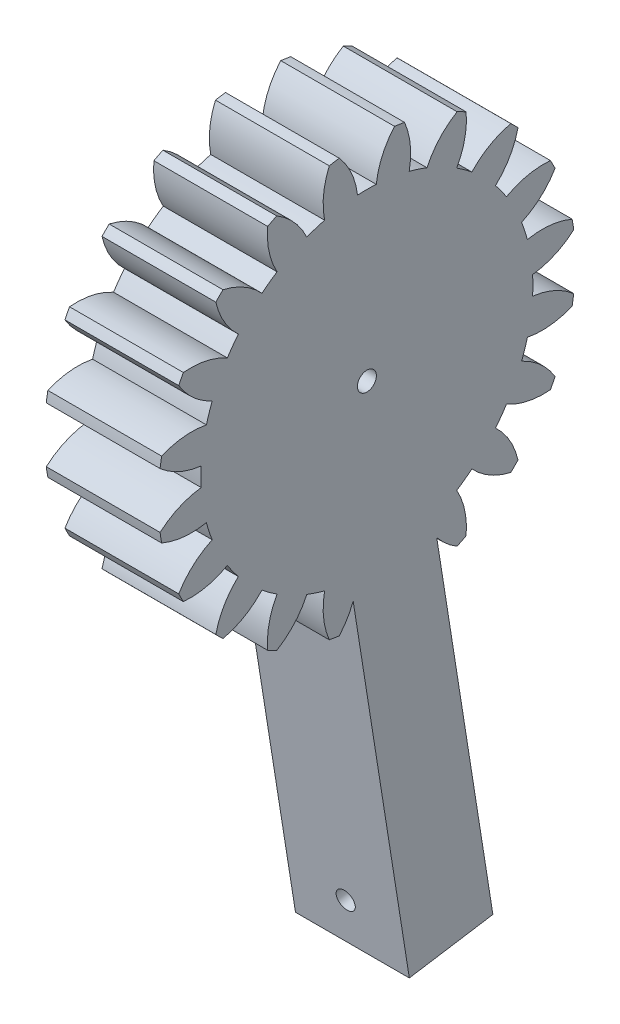
SolidWorks part; units mm, degrees
ref_plane "Plane1" through (0, 0, 0) normal (0, 0, 1) x (1, 0, 0)
ref_plane "Plane2" through (0, 0, 0) normal (0, 1, 0) x (1, 0, 0)
ref_plane "Plane3" through (0, 0, 0) normal (1, 0, 0) x (0, 0, -1)
other "Configuration Table"
sketch "HoldingSke" plane through (0, 0, 0) normal (0, 1, 0) x (1, 0, 0)
  line L0 (0, 0) -> (0.1879, -0.0684)
  line L1 (-15, 0) -> (100, 0) construction
  line L2 (0, 0) -> (-2.1039, 2.3779)
  line L3 (0, 0) -> (-11.863, 4.5341)
  line L4 (0, 0) -> (8.1152, 2.9537)
  line L5 (0, 0) -> (-46.8476, -17.4728)
  line L6 (0, 0) -> (-24.8689, -16.7791)
  line L7 (-2.1039, 2.3779) -> (8.6586, 51.2059)
  line L8 (-76.2, 54.61) -> (-75.3, 54.61)
  line L9 (-71.009, 38.7566) -> (-53.1078, 45.2721)
  line L10 (-76.2, 71.12) -> (104.1128, 71.12)
  line L11 (0, 0) -> (-30, 0)
  line L12 (-76.2, 101.6) -> (-76.033, 101.6)
  line L13 (24.9733, 27.94) -> (52.9518, 28.4284)
  line L14 (24.9733, 27.94) -> (24.9743, 27.94)
  line L15 (24.9733, 27.94) -> (100.4006, 29.5858)
  line L16 (-63.627, -5) -> (-12.827, -5)
  circle A0 centre (0, 0) radius 2.5
  circle A1 centre (0, 0) radius 37.5
  circle A2 centre (0, 0) radius 37.5
  circle A3 centre (0, 0) radius 2.5
  dimension "MHD" = 75
  dimension "Hub_dia" = 75
  dimension "Bore" = 5
  dimension "MBD" = 5
  dimension "Num_teeth" = 20
  dimension "Pitch" = 0.2
  dimension "Overall_len" = 50
  dimension "Show_teeth" = 20
  dimension "Thickness" = 30
  dimension "OAL" = 50.0001
  dimension "T_dim" = 0.9
  dimension "Ap" = 20
  dimension "H" = 19.05
  dimension "Pitch_radius" = 180.3128
  dimension "Width" = 30
  dimension "Backlash" = 0.167
  dimension "Addendum_fac" = 1
  dimension "Dedendum_fac" = 1.25
  dimension "Clearance_fac" = 0.25
  dimension "Dedendum_add" = 0.001
  dimension "Module" = 5
sketch "BasProSke" plane through (0, 0, 0) normal (0, 1, 0) x (1, 0, 0)
  line L0 (-10, 0) -> (60, 0) construction
  line L1 (0, 0) -> (0, 55)
  line L2 (0, 0) -> (30, 0)
  line L3 (30, 0) -> (30, 55)
  line L4 (30, 55) -> (0, 55)
  dimension "Thickness" = 30
  dimension "Diameter" = 110
revolve "Base-Revolve" add sketch "BasProSke" angle 360 about L0
sketch "TooCutSke" plane through (0, 0, 0) normal (1, 0, 0) x (0, 0, -1)
  line L1 (0, 0) -> (0, 107) construction
  line L2 (0, 0) -> (-4.2151, 49.822) construction
  line L3 (0, 0) -> (-15.6021, 98.5081) construction
  line L4 (-4.2151, 49.822) -> (-7.8011, 49.254) construction
  arc A0 (2.4648, 43.6795) -> (-2.4648, 43.6795) centre (0, 0) ccw
  arc A1 (7.3009, 54.5389) -> (-7.3009, 54.5389) centre (0, 0) ccw
  circle A2 centre (0, 0) radius 50 construction
  circle A3 centre (0, 0) radius 46.9846 construction
  arc A4 (-2.4648, 43.6795) -> (-7.3009, 54.5389) centre (-22.3276, 41.3405) ccw
  arc A5 (7.3009, 54.5389) -> (2.4648, 43.6795) centre (22.3276, 41.3405) ccw
  dimension "Root_dia" = 87.498
  dimension "Overcut_dia" = 110.0508
  dimension "Pitch_dia" = 100
  dimension "Base_dia" = 93.9693
  dimension "Flank_rad" = 20
  dimension "Half_ang" = 9
  dimension "Half_CT" = 3.6307
extrude "ToothCut" cut sketch "TooCutSke" along normal through all
fillet "Breaks" [suppressed] radius 0.1
fillet "RootFillets" [suppressed] radius 1.251
pattern_circular "TeethCuts" count 20 over 360 about axis through (0, 0, 0) along (1, 0, 0) of "ToothCut", "RootFillets", "Breaks"
sketch "HubNeaOneSke" plane through (0, 0, 0) normal (-1, 0, 0) x (0, 0, 1)
  circle A0 centre (0, 0) radius 37.5
  dimension "Diameter" = 75
extrude "HubNearOne" [suppressed] add sketch "HubNeaOneSke" along normal blind 20.0001
sketch "HubNeaBotSke" plane through (0, 0, 0) normal (-1, 0, 0) x (0, 0, 1)
  circle A0 centre (0, 0) radius 37.5
  dimension "Diameter" = 75
extrude "HubNearBoth" [suppressed] add sketch "HubNeaBotSke" along normal blind 10
ref_plane "FarPln" through (30, 0, 0) normal (1, 0, 0) x (0, 0, -1)
sketch "HubFarSke" plane through (30, 0, 0) normal (1, 0, 0) x (0, 0, -1)
  circle A0 centre (0, 0) radius 37.5
  dimension "Diameter" = 75
extrude "HubFar" [suppressed] add sketch "HubFarSke" along normal blind 10
sketch "BorSke" plane through (0, 0, 0) normal (1, 0, 0) x (0, 0, -1)
  circle A0 centre (0, 0) radius 2.5
  dimension "Diameter" = 5
extrude "Bore" cut sketch "BorSke" along normal mid plane 100.0001
sketch "KeySke" plane through (0, 0, 0) normal (1, 0, 0) x (0, 0, -1)
  line L0 (-1, 0) -> (-1, 3.4)
  line L1 (-1, 3.4) -> (1, 3.4)
  line L2 (1, 3.4) -> (1, 0)
  line L3 (0, 0) -> (0, 34) construction
  line L4 (-1, 0) -> (1, 0)
  dimension "Offset" = 3.4
  dimension "Width" = 2
extrude "Keyway" [suppressed] cut sketch "KeySke" along normal mid plane 100.0001
pattern_circular "Keyway2" [suppressed] count 2 every 90 about axis through (-10, 0, 0) along (1, 0, 0)
sketch "草图6" plane through (30, 0, 0) normal (1, 0, 0) x (0, 0, -1)
  line L3 (0, 50) -> (0, -50) construction
  line L4 (0, 0) -> (6.8439, -43.2104) construction
  line L5 (-4.4661, -43.0812) -> (11.1773, -141.85)
  line L6 (11.1773, -141.85) -> (33.2038, -138.3614)
  line L7 (33.2038, -138.3614) -> (17.5603, -39.5926)
  circle A0 centre (0, 0) radius 43.297 construction
  arc A2 (-4.4661, -43.0812) -> (17.5603, -39.5926) centre (-0.0707, 0.4464) ccw
  point P5 (-247.4407, -93.586)
  point P11 (0, 0)
  dimension "D2" = 22.301
  dimension "D3" = 0.452
  dimension "D4" = 86.594
  dimension "D5" = 43.749
  dimension "D1" = 100
extrude "凸台-拉伸1" add sketch "草图6" against normal up to surface (30 mm away) up to face at (0, 0, -2.5)
sketch "草图7" plane through (0, -1.7443, 11.0132) normal (0, -0.1564, 0.9877) x (1, 0, 0)
  line L0 (0, -141.8521) -> (30, -141.8521) construction
  line L3 (15, -141.8521) -> (15, -66.61) construction
  circle A0 centre (15, -130.5681) radius 2.5
  dimension "D1" = 5
  dimension "D2" = 11.284
extrude "切除-拉伸1" cut sketch "草图7" against normal through all both and the other way through all
equation "' \"Module@HoldingSke\" = 6.35"
equation "' \"Num_teeth@HoldingSke\" = 12"
equation "' \"Ap@HoldingSke\" =  20"
equation "' \"Ap@HoldingSke\" = 20"
equation "' \"Width@HoldingSke\" = 0.5 * 25.4"
equation "' \"Hub_dia@HoldingSke\"= 1 * 25.4"
equation "' \"Hub_dia@HoldingSke\" = 1 * 25.4"
equation "' \"Overall_len@HoldingSke\" = 1.0 * 25.4"
equation "' \"Bore@HoldingSke\" = 0.75 * 25.4"
equation "' \"T_dim@HoldingSke\" = 0.1 * 25.4"
equation "' \"Width@KeySke\" = 0.25 * 25.4"
equation "' \"Show_teeth@HoldingSke\" = 13"
equation "' \"Backlash@HoldingSke\" = 0.009 * 25.4"
equation "' \"Addendum_fac@HoldingSke\" = 1.0"
equation "' \"Dedendum_fac@HoldingSke\" = 1.25"
equation "' \"Dedendum_add@HoldingSke\" = 0.00005 * 25.4"
equation "' \"Clearance_fac@HoldingSke\" = 0.25"
equation "\"Pitch@HoldingSke\" = 1 / \"Module@HoldingSke\""
equation "\"Overcut_dia@TooCutSke\" = (\"Num_teeth@HoldingSke\" + 2 * \"Addendum_fac@HoldingSke\") / \"Pitch@HoldingSke\" + 0.002 * 25.4"
equation "\"Pitch_dia@TooCutSke\" = \"Num_teeth@HoldingSke\" / \"Pitch@HoldingSke\""
equation "\"Base_dia@TooCutSke\" = \"Num_teeth@HoldingSke\" / \"Pitch@HoldingSke\" * cos((\"Ap@HoldingSke\"  * 3.14159265 / 180))"
equation "\"Root_dia@TooCutSke\" = (\"Num_teeth@HoldingSke\" + 2) / \"Pitch@HoldingSke\" - 2 * (\"Addendum_fac@HoldingSke\" + \"Dedendum_fac@HoldingSke\") / \"Pitch@HoldingSke\" - \"Dedendum_add@HoldingSke\" * 2"
equation "\"Half_ang@TooCutSke\" = 180 / \"Num_teeth@HoldingSke\""
equation "\"Half_CT@TooCutSke\" = \"Num_teeth@HoldingSke\" / \"Pitch@HoldingSke\" * sin((3.14159265 / 2 / \"Num_teeth@HoldingSke\")) / 2 - 7 * \"Backlash@HoldingSke\" / 4"
equation "\"Flank_rad@TooCutSke\" = \"Num_teeth@HoldingSke\" / \"Pitch@HoldingSke\" / 5"
equation "\"Radius@RootFillets\" = \"Clearance_fac@HoldingSke\" / \"Pitch@HoldingSke\" + \"Dedendum_add@HoldingSke\""
equation "\"Break_rad@Breaks\" = 0.02 / \"Pitch@HoldingSke\""
equation "\"Thickness@HoldingSke\" = \"Width@HoldingSke\""
equation "\"OAL@HoldingSke\" = \"Thickness@HoldingSke\""
equation "\"MHD@HoldingSke\" = (\"Num_teeth@HoldingSke\" + 2) / \"Pitch@HoldingSke\" - 2 * (\"Addendum_fac@HoldingSke\" + \"Dedendum_fac@HoldingSke\")  / \"Pitch@HoldingSke\" - \"Dedendum_add@HoldingSke\" * 2"
equation "\"MBD@HoldingSke\" = (\"Num_teeth@HoldingSke\" + 2) / \"Pitch@HoldingSke\" - 2 * (\"Addendum_fac@HoldingSke\" + \"Dedendum_fac@HoldingSke\")  / \"Pitch@HoldingSke\" - \"Dedendum_add@HoldingSke\" * 2 - 0.002 * 25.4"
equation "\"MHD@HoldingSke\" = ((sgn( \"MHD@HoldingSke\" - \"Hub_dia@HoldingSke\" )-1)*( \"MHD@HoldingSke\" - \"Hub_dia@HoldingSke\" ))/-2+ \"Hub_dia@HoldingSke\""
equation "\"MBD@HoldingSke\" = ((sgn( \"MBD@HoldingSke\" - \"Bore@HoldingSke\" )-1)*( \"MBD@HoldingSke\" - \"Bore@HoldingSke\" ))/-2+ \"Bore@HoldingSke\""
equation "\"OAL@HoldingSke\" = ((sgn( \"OAL@HoldingSke\" - \"Overall_len@HoldingSke\" )+1)*( \"OAL@HoldingSke\" - \"Overall_len@HoldingSke\" ))/2 + \"Overall_len@HoldingSke\" + 0.000002 * 25.4"
equation "\"Num_teeth@TeethCuts\" = int( \"Show_teeth@HoldingSke\" ) + 1"
equation "\"Num_teeth@TeethCuts\" = ((sgn( \"Num_teeth@TeethCuts\" - \"Num_teeth@HoldingSke\" )-1)*( \"Num_teeth@TeethCuts\" - \"Num_teeth@HoldingSke\" ))/-2+ \"Num_teeth@HoldingSke\""
equation "\"Num_teeth@TeethCuts\" = ((sgn( \"Num_teeth@TeethCuts\" - 2.0)+1)*( \"Num_teeth@TeethCuts\" - 2.0))/2 +2.0"
equation "\"Angle@TeethCuts\" = 360.0 / \"Num_teeth@HoldingSke\""
equation "\"Diameter@BasProSke\" = (\"Num_teeth@HoldingSke\" + 2 * \"Addendum_fac@HoldingSke\") / \"Pitch@HoldingSke\""
equation "\"Thickness@BasProSke\"  = \"Thickness@HoldingSke\""
equation "' \"Fillet_rad@BasProSke\" =  \"Thickness@HoldingSke\" * 0.05"
equation "' \"Fillet_rad@BasProSke\" = \"Thickness@HoldingSke\" * 0.05"
equation "\"MHD@HoldingSke\" = ((sgn( \"MHD@HoldingSke\" - \"Root_dia@TooCutSke\" )-1)*( \"MHD@HoldingSke\" - \"Root_dia@TooCutSke\" ))/-2+ \"Root_dia@TooCutSke\""
equation "\"Diameter@HubNeaOneSke\" = \"MHD@HoldingSke\""
equation "\"Length@HubNearOne\" = \"OAL@HoldingSke\" - \"Thickness@BasProSke\""
equation "\"Diameter@HubNeaBotSke\" = \"MHD@HoldingSke\""
equation "\"Length@HubNearBoth\" = ( \"OAL@HoldingSke\" - \"Thickness@BasProSke\" ) / 2.0"
equation "\"Thickness@FarPln\" = \"Thickness@BasProSke\""
equation "\"Diameter@HubFarSke\" = \"MHD@HoldingSke\""
equation "\"Length@HubFar\" = ( \"OAL@HoldingSke\" - \"Thickness@BasProSke\" ) / 2.0"
equation "\"Diameter@BorSke\" = \"MBD@HoldingSke\""
equation "\"D1@Bore\" = \"OAL@HoldingSke\" * 2.0"
equation "\"D1@Keyway\" = \"OAL@HoldingSke\" * 2.0"
equation "\"Offset@KeySke\" = \"T_dim@HoldingSke\" + \"MBD@HoldingSke\" / 2.0"
